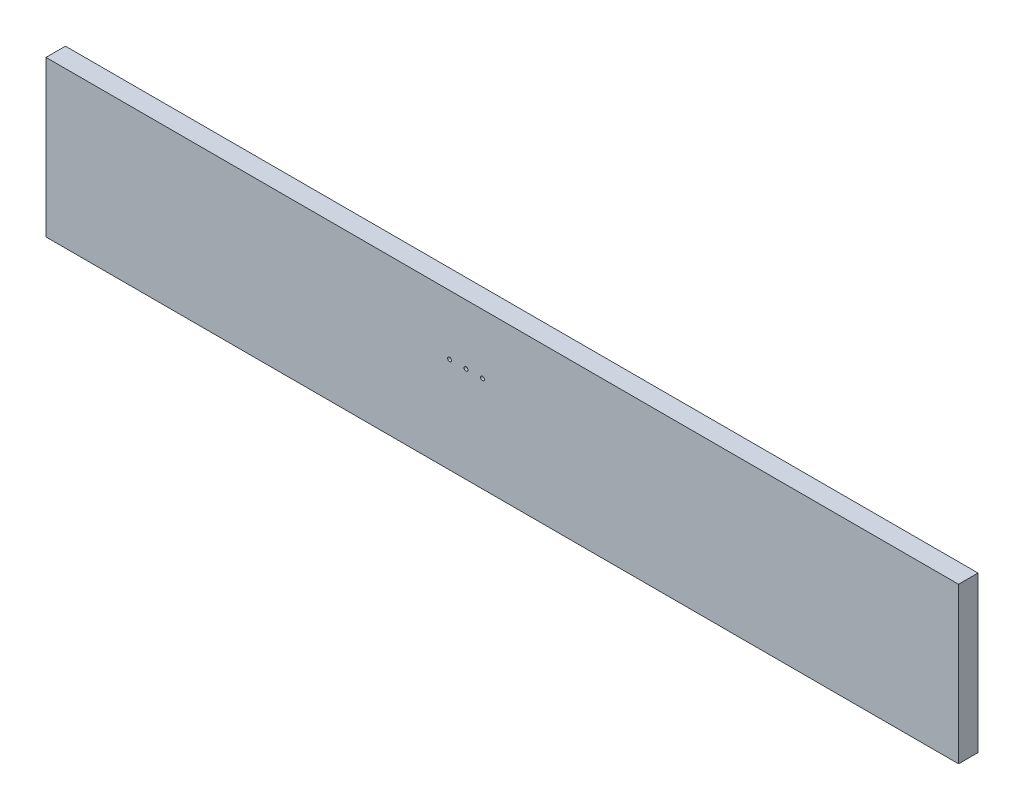
SolidWorks part; units mm, degrees
ref_plane "前视基准面" through (0, 0, 0) normal (0, 0, 1) x (1, 0, 0)
ref_plane "上视基准面" through (0, 0, 0) normal (0, 1, 0) x (1, 0, 0)
ref_plane "右视基准面" through (0, 0, 0) normal (1, 0, 0) x (0, 0, -1)
sketch "草图1" plane through (0, 0, 0) normal (0, 0, 1) x (1, 0, 0)
  line L1 (-352, 60) -> (352, 60)
  line L2 (-352, 60) -> (-352, -60)
  line L3 (-352, -60) -> (352, -60)
  line L4 (352, 60) -> (352, -60)
  line L5 (-352, 60) -> (352, -60) construction
  line L6 (-352, -60) -> (352, 60) construction
  point P0 (0, 0)
  dimension "D1" = 120
  dimension "D2" = 704
extrude "凸台-拉伸1" add sketch "草图1" along normal blind 15
sketch "草图2" plane through (0, 0, 15) normal (0, 0, 1) x (1, 0, 0)
  line L0 (352, 60) -> (-352, 60) construction
  line L1 (352, -60) -> (352, 60) construction
  circle A0 centre (-15.29, 13.9) radius 1.5
  circle A1 centre (-27.99, 13.9) radius 1.5
  circle A2 centre (-40.69, 13.9) radius 1.5
  dimension "D2" = 367.29
  dimension "D3" = 3
  dimension "D1" = 46.1
  dimension "D5" = 12.7
  dimension "D4" = 3
extrude "切除-拉伸1" cut sketch "草图2" against normal through all
